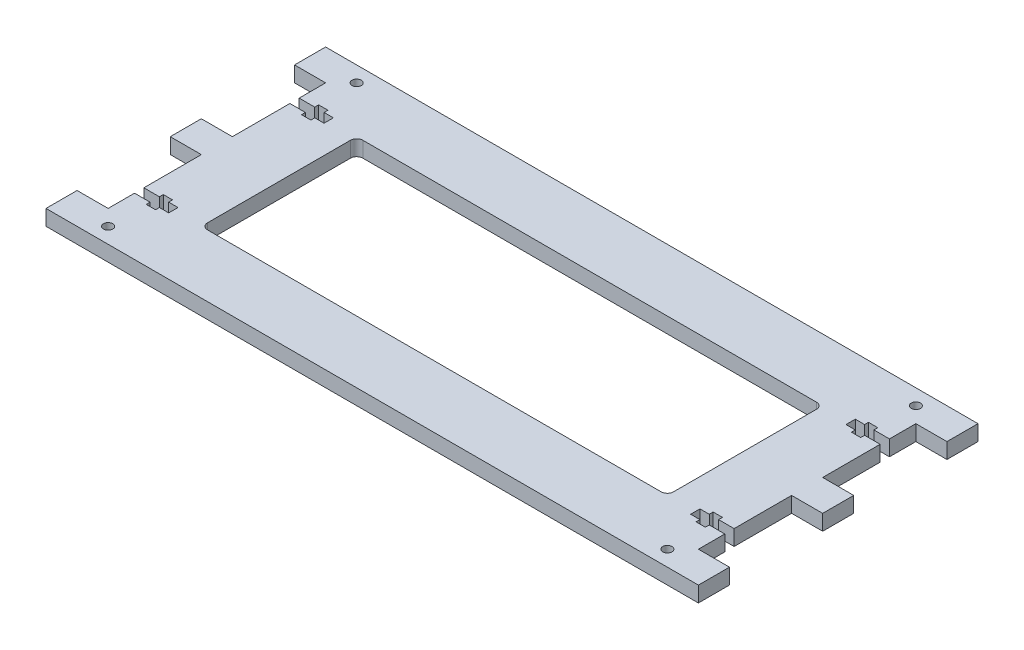
SolidWorks part; units mm, degrees
material "Maple"
ref_plane "Front Plane" through (0, 0, 0) normal (0, 0, 1) x (1, 0, 0)
ref_plane "Top Plane" through (0, 0, 0) normal (0, 1, 0) x (1, 0, 0)
ref_plane "Right Plane" through (0, 0, 0) normal (1, 0, 0) x (0, 0, -1)
sketch "Sketch1" plane through (0, 0, 0) normal (0, 1, 0) x (1, 0, 0)
  line L0 (-95, -45) -> (95, 45) construction
  line L2 (-90, 40) -> (90, 40) construction
  line L3 (-90, 40) -> (-90, -40) construction
  line L4 (-90, -40) -> (90, -40) construction
  line L5 (-95, 45) -> (-95, -45)
  line L6 (-95, -45) -> (95, -45)
  line L7 (95, -45) -> (95, 45)
  line L10 (-95, 45) -> (95, 45)
  line L13 (90, 40) -> (90, -40) construction
  line L14 (-75, 25) -> (75, 25)
  line L15 (-75, 25) -> (-75, -25)
  line L16 (-75, -25) -> (75, -25)
  line L17 (75, 25) -> (75, -25)
  circle A0 centre (-90, 40) radius 1.5
  circle A1 centre (-90, -40) radius 1.5
  circle A2 centre (90, 40) radius 1.5
  circle A3 centre (90, -40) radius 1.5
  point P0 (0, 0)
  point P18 (95, 0)
  dimension "D3" = 3
  dimension "D1" = 190
  dimension "D2" = 20
  dimension "D4" = 5
  dimension "D5" = 90
  dimension "D6" = 5
  dimension "D7" = 20
  dimension "D8" = 5
  dimension "D9" = 5
  dimension "D10" = 20
  dimension "D11" = 20
extrude "Boss-Extrude1" add sketch "Sketch1" along normal blind 5
fillet "Fillet1" radius 2 4 edges at (75, 2.5, -25) (75, 2.5, 25) (-75, 2.5, 25) (-75, 2.5, -25)
sketch "Sketch2" plane through (0, 5, 0) normal (0, 1, 0) x (1, 0, 0)
  line L0 (95, -23.5) -> (90, -23.5)
  line L1 (90, -23.5) -> (90, -22.25)
  line L2 (90, -22.25) -> (87, -22.25)
  line L3 (87, -22.25) -> (87, -23.5)
  line L4 (87, -23.5) -> (84, -23.5)
  line L5 (84, -23.5) -> (84, -26.5)
  line L6 (84, -26.5) -> (87, -26.5)
  line L7 (87, -26.5) -> (87, -27.75)
  line L8 (87, -27.75) -> (90, -27.75)
  line L9 (90, -27.75) -> (90, -26.5)
  line L10 (90, -26.5) -> (95, -26.5)
  line L11 (95, -26.5) -> (95, -23.5)
  line L12 (95, -45) -> (95, 45) construction
  line L13 (84, -25) -> (95, -25) construction
  line L14 (-95, -45) -> (95, -45) construction
  line L15 (0, 0) -> (0, 45) construction
  line L16 (95, 45) -> (-95, 45) construction
  line L17 (0, 0) -> (95, 0) construction
  line L18 (84, 25) -> (95, 25) construction
  line L19 (95, 26.5) -> (95, 23.5)
  line L20 (90, 26.5) -> (95, 26.5)
  line L21 (90, 27.75) -> (90, 26.5)
  line L22 (87, 27.75) -> (90, 27.75)
  line L23 (87, 26.5) -> (87, 27.75)
  line L24 (84, 26.5) -> (87, 26.5)
  line L25 (84, 23.5) -> (84, 26.5)
  line L26 (87, 23.5) -> (84, 23.5)
  line L27 (87, 22.25) -> (87, 23.5)
  line L28 (90, 22.25) -> (87, 22.25)
  line L29 (90, 23.5) -> (90, 22.25)
  line L30 (95, 23.5) -> (90, 23.5)
  line L31 (-84, 25) -> (-95, 25) construction
  line L32 (-84, -25) -> (-95, -25) construction
  line L33 (-95, 23.5) -> (-90, 23.5)
  line L34 (-90, 23.5) -> (-90, 22.25)
  line L35 (-90, 22.25) -> (-87, 22.25)
  line L36 (-87, 22.25) -> (-87, 23.5)
  line L37 (-87, 23.5) -> (-84, 23.5)
  line L38 (-84, 23.5) -> (-84, 26.5)
  line L39 (-84, 26.5) -> (-87, 26.5)
  line L40 (-87, 26.5) -> (-87, 27.75)
  line L41 (-87, 27.75) -> (-90, 27.75)
  line L42 (-90, 27.75) -> (-90, 26.5)
  line L43 (-90, 26.5) -> (-95, 26.5)
  line L44 (-95, 26.5) -> (-95, 23.5)
  line L45 (-95, -26.5) -> (-95, -23.5)
  line L46 (-90, -26.5) -> (-95, -26.5)
  line L47 (-90, -27.75) -> (-90, -26.5)
  line L48 (-87, -27.75) -> (-90, -27.75)
  line L49 (-87, -26.5) -> (-87, -27.75)
  line L50 (-84, -26.5) -> (-87, -26.5)
  line L51 (-84, -23.5) -> (-84, -26.5)
  line L52 (-87, -23.5) -> (-84, -23.5)
  line L53 (-87, -22.25) -> (-87, -23.5)
  line L54 (-90, -22.25) -> (-87, -22.25)
  line L55 (-90, -23.5) -> (-90, -22.25)
  line L56 (-95, -23.5) -> (-90, -23.5)
  point P13 (92.5, -26.5)
  dimension "D1" = 3
  dimension "D2" = 3
  dimension "D3" = 3
  dimension "D4" = 5
  dimension "D5" = 5.5
  dimension "D6" = 20
extrude "Cut-Extrude1" cut sketch "Sketch2" against normal through all
sketch "Sketch3" plane through (0, 5, 0) normal (0, 1, 0) x (1, 0, 0)
  line L0 (95, -23.5) -> (95, 23.5) construction
  line L1 (95, 45) -> (105, 45)
  line L2 (95, 45) -> (95, 35)
  line L3 (95, 35) -> (105, 35)
  line L4 (105, 45) -> (105, 35)
  line L5 (95, 5) -> (105, 5)
  line L6 (95, 5) -> (95, -5)
  line L7 (95, -5) -> (105, -5)
  line L8 (105, 5) -> (105, -5)
  line L9 (0, 0) -> (0, 45) construction
  line L10 (95, -45) -> (105, -45)
  line L11 (95, -45) -> (95, -35)
  line L12 (95, -35) -> (105, -35)
  line L13 (105, -45) -> (105, -35)
  line L14 (95, 45) -> (-95, 45) construction
  line L15 (95, 0) -> (0, 0) construction
  line L16 (-105, -45) -> (-105, -35)
  line L17 (-95, -35) -> (-105, -35)
  line L18 (-95, -45) -> (-95, -35)
  line L19 (-95, -45) -> (-105, -45)
  line L20 (-105, 5) -> (-105, -5)
  line L21 (-95, -5) -> (-105, -5)
  line L22 (-95, 5) -> (-95, -5)
  line L23 (-95, 5) -> (-105, 5)
  line L24 (-105, 45) -> (-105, 35)
  line L25 (-95, 35) -> (-105, 35)
  line L26 (-95, 45) -> (-95, 35)
  line L27 (-95, 45) -> (-105, 45)
  dimension "D1" = 10
  dimension "D2" = 10
extrude "Boss-Extrude2" add sketch "Sketch3" against normal up to surface (5 mm away) up to face at (0, 0, 0)
